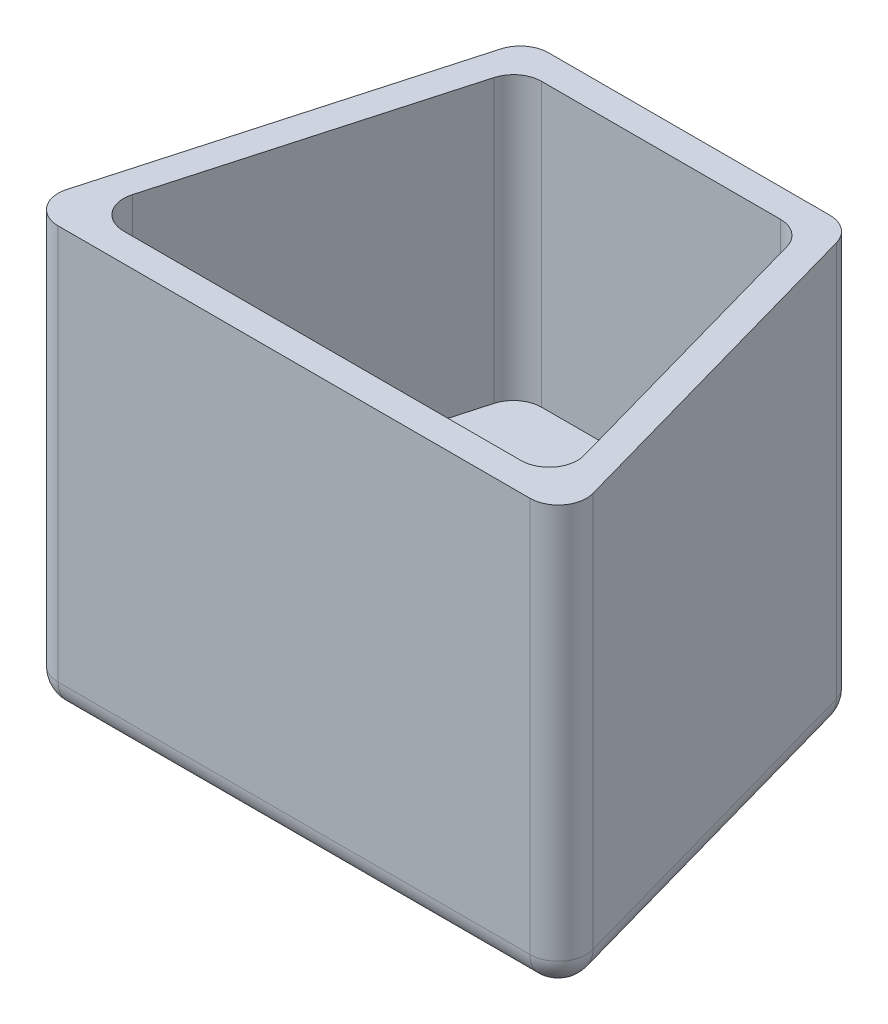
SolidWorks part; units mm, degrees
ref_plane "Front Plane" through (0, 0, 0) normal (0, 0, 1) x (1, 0, 0)
ref_plane "Top Plane" through (0, 0, 0) normal (0, 1, 0) x (1, 0, 0)
ref_plane "Right Plane" through (0, 0, 0) normal (1, 0, 0) x (0, 0, -1)
sketch "Sketch1" plane through (0, 0, 0) normal (0, 1, 0) x (1, 0, 0)
  line L1 (-8.3599, -7) -> (8.3599, -7)
  line L5 (5.9476, 6.2707) -> (9.3226, -5.7293)
  line L6 (-4.9849, 7) -> (4.9849, 7)
  line L7 (-5.9476, 6.2707) -> (-9.3226, -5.7293)
  line L8 (-7.0399, -6) -> (7.0399, -6)
  line L9 (5.19, 5.2707) -> (8.0025, -4.7293)
  line L10 (-4.2274, 6) -> (4.2274, 6)
  line L11 (-5.19, 5.2707) -> (-8.0025, -4.7293)
  line L12 (-4.9849, 6) -> (-8.3599, -6) construction
  line L13 (-8.3599, -6) -> (8.3599, -6) construction
  line L14 (4.9849, 6) -> (8.3599, -6) construction
  line L15 (-4.9849, 6) -> (4.9849, 6) construction
  arc A4 (8.3599, -7) -> (9.3226, -5.7293) centre (8.3599, -6) ccw
  arc A5 (4.9849, 7) -> (5.9476, 6.2707) centre (4.9849, 6) cw
  arc A6 (-4.9849, 7) -> (-5.9476, 6.2707) centre (-4.9849, 6) ccw
  arc A7 (-8.3599, -7) -> (-9.3226, -5.7293) centre (-8.3599, -6) cw
  arc A8 (5.19, 5.2707) -> (4.2274, 6) centre (4.2274, 5) ccw
  arc A9 (-4.2274, 6) -> (-5.19, 5.2707) centre (-4.2274, 5) ccw
  arc A11 (8.0025, -4.7293) -> (7.0399, -6) centre (7.0399, -5) cw
  arc A12 (-8.0025, -4.7293) -> (-7.0399, -6) centre (-7.0399, -5) ccw
  arc A13 (-8.3599, -6) -> (-8.3599, -6) centre (-8.3599, -6) cw construction
  arc A14 (8.3599, -6) -> (8.3599, -6) centre (8.3599, -6) ccw construction
  arc A15 (4.9849, 6) -> (4.9849, 6) centre (4.9849, 6) cw construction
  arc A16 (-4.9849, 6) -> (-4.9849, 6) centre (-4.9849, 6) ccw construction
  dimension "D2" = 1
  dimension "D1" = 1
extrude "Boss-Extrude1" add sketch "Sketch1" along normal blind 15
sketch "Sketch2" plane through (0, 0, 0) normal (0, -1, 0) x (1, 0, 0)
  line L4 (-9.3226, 5.7293) -> (-5.9476, -6.2707)
  line L5 (-4.9849, -7) -> (4.9849, -7)
  line L6 (5.9476, -6.2707) -> (9.3226, 5.7293)
  line L7 (8.3599, 7) -> (-8.3599, 7)
  line L8 (-9.3226, 5.7293) -> (-5.9476, -6.2707)
  line L9 (-4.9849, -7) -> (4.9849, -7)
  line L10 (5.9476, -6.2707) -> (9.3226, 5.7293)
  line L11 (8.3599, 7) -> (-8.3599, 7)
  arc A4 (-8.3599, 7) -> (-9.3226, 5.7293) centre (-8.3599, 6) ccw
  arc A5 (-5.9476, -6.2707) -> (-4.9849, -7) centre (-4.9849, -6) ccw
  arc A6 (4.9849, -7) -> (5.9476, -6.2707) centre (4.9849, -6) ccw
  arc A7 (9.3226, 5.7293) -> (8.3599, 7) centre (8.3599, 6) ccw
  arc A8 (-8.3599, 7) -> (-9.3226, 5.7293) centre (-8.3599, 6) ccw
  arc A9 (-5.9476, -6.2707) -> (-4.9849, -7) centre (-4.9849, -6) ccw
  arc A10 (4.9849, -7) -> (5.9476, -6.2707) centre (4.9849, -6) ccw
  arc A11 (9.3226, 5.7293) -> (8.3599, 7) centre (8.3599, 6) ccw
  dimension "D1" = 0
extrude "Boss-Extrude2" add sketch "Sketch2" against normal blind 5
fillet "Fillet1" radius 1 8 edges at (-9.157, 0, 6.6038) (-7.6351, 0, -0.2707) (-5.5887, 0, -6.7971) (0, 0, -7) (5.5887, 0, -6.7971) (7.6351, 0, -0.2707) (9.157, 0, 6.6038) (0, 0, 7)
